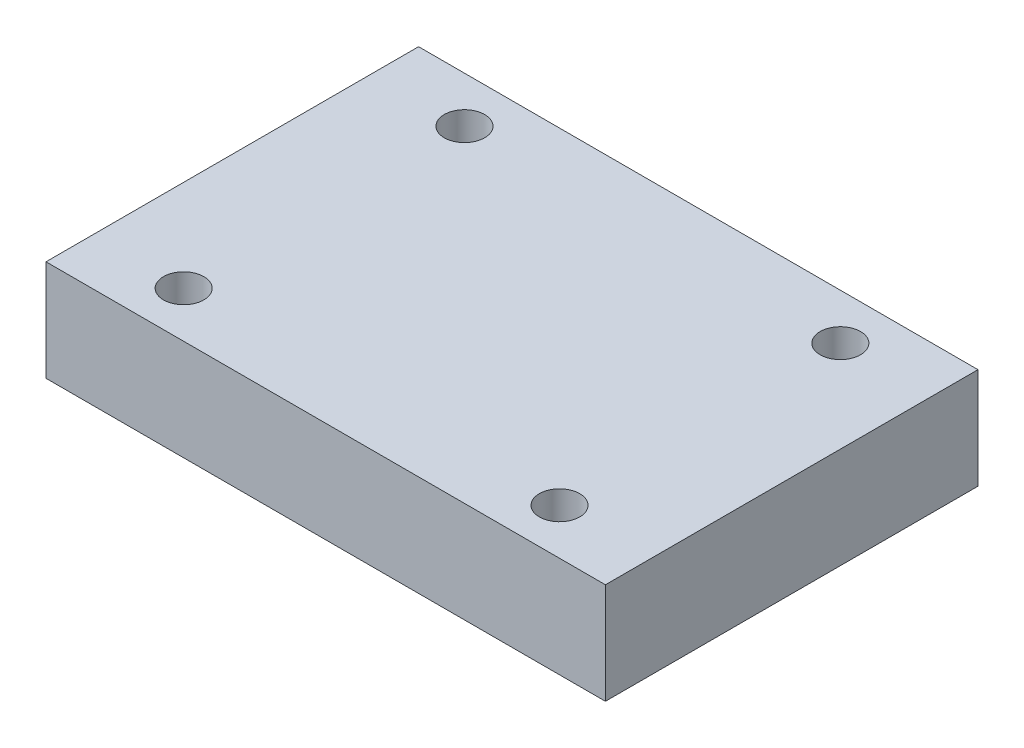
SolidWorks part; units mm, degrees
ref_plane "Front Plane" through (0, 0, 0) normal (0, 0, 1) x (1, 0, 0)
ref_plane "Top Plane" through (0, 0, 0) normal (0, 1, 0) x (1, 0, 0)
ref_plane "Right Plane" through (0, 0, 0) normal (1, 0, 0) x (0, 0, -1)
sketch "Sketch1" plane through (0, 0, 0) normal (0, 1, 0) x (1, 0, 0)
  line L1 (0, 0) -> (30.48, 0)
  line L2 (0, 0) -> (0, 20.3)
  line L3 (0, 20.3) -> (30.48, 20.3)
  line L4 (30.48, 0) -> (30.48, 20.3)
  circle A0 centre (5, 17.8) radius 1.1
  circle A1 centre (25.48, 17.8) radius 1.1
  circle A2 centre (25.48, 2.5) radius 1.1
  circle A3 centre (5, 2.5) radius 1.1
  dimension "D3" = 2.2
  dimension "D1" = 30.48
  dimension "D2" = 20.3
  dimension "D4" = 2.5
  dimension "D5" = 2.5
  dimension "D6" = 5
  dimension "D7" = 5
extrude "Boss-Extrude1" add sketch "Sketch1" along normal blind 5.5
